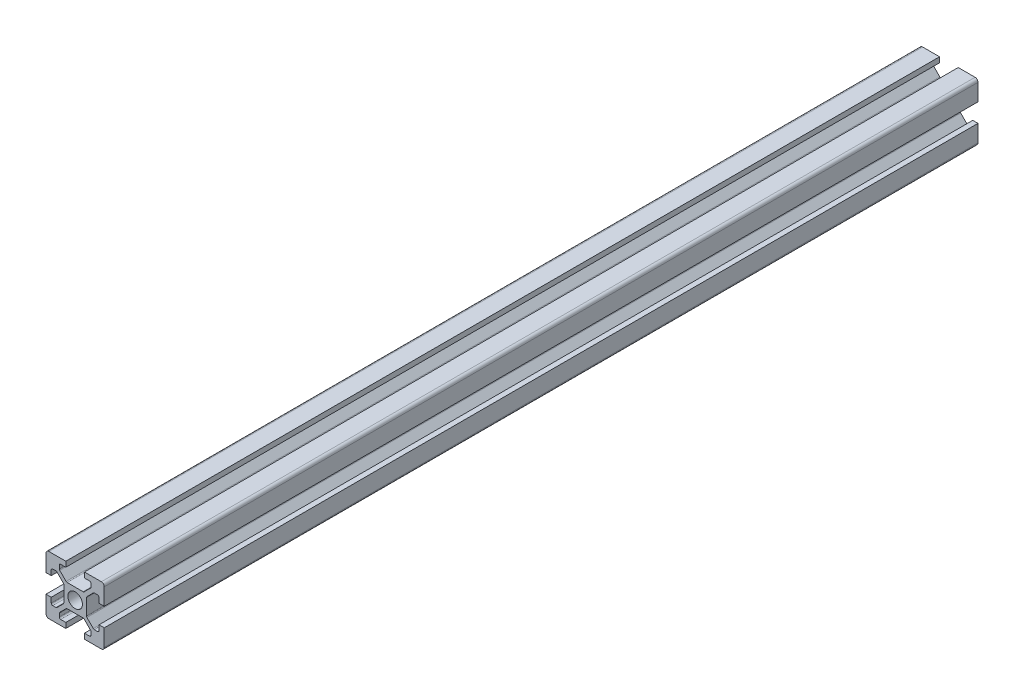
SolidWorks part; units mm, degrees
material "1060 Alloy"
ref_plane "Front Plane" through (0, 0, 0) normal (0, 0, 1) x (1, 0, 0)
ref_plane "Top Plane" through (0, 0, 0) normal (0, 1, 0) x (1, 0, 0)
ref_plane "Right Plane" through (0, 0, 0) normal (1, 0, 0) x (0, 0, -1)
sketch "Sketch1" plane through (0, 0, 0) normal (0, 0, 1) x (1, 0, 0)
  line L0 (20, 0) -> (-8.059, 28.059) construction
  line L1 (0, 0) -> (6.8, 0)
  line L2 (0, 0) -> (0, 6.8)
  line L3 (0, 20) -> (6.8, 20)
  line L4 (20, 0) -> (20, 6.8)
  line L5 (6.8, 20) -> (6.8, 18.2)
  line L6 (20, 20) -> (8.2322, 8.2322) construction
  line L7 (12.95, 6.1) -> (7.05, 6.1)
  line L8 (13.9, 7.05) -> (13.9, 12.95)
  line L9 (12.95, 13.9) -> (7.05, 13.9)
  line L10 (6.1, 7.05) -> (6.1, 12.95)
  line L11 (13.9, 6.1) -> (6.1, 13.9) construction
  line L12 (13.9, 13.9) -> (6.1, 6.1) construction
  line L13 (4.55, 16.4) -> (7.05, 13.9)
  line L14 (13.2, 18.2) -> (13.2, 20)
  line L15 (1.8, 6.8) -> (0, 6.8)
  line L16 (0, 13.2) -> (0, 20)
  line L17 (0, 13.2) -> (1.8, 13.2)
  line L18 (10, 10) -> (10, 13.9) construction
  line L19 (16.4, 4.55) -> (13.9, 7.05)
  line L20 (4.55, 16.4) -> (4.55, 18.2)
  line L21 (4.55, 18.2) -> (6.8, 18.2)
  line L22 (13.2, 18.2) -> (15.45, 18.2)
  line L23 (15.45, 18.2) -> (15.45, 16.4)
  line L24 (15.45, 16.4) -> (12.95, 13.9)
  line L25 (16.4, 4.55) -> (18.2, 4.55)
  line L26 (18.2, 4.55) -> (18.2, 6.8)
  line L27 (20, 6.8) -> (18.2, 6.8)
  line L28 (18.2, 13.2) -> (20, 13.2)
  line L29 (18.2, 13.2) -> (18.2, 15.45)
  line L30 (18.2, 15.45) -> (16.4, 15.45)
  line L31 (16.4, 15.45) -> (13.9, 12.95)
  line L32 (1.8, 4.55) -> (3.6, 4.55)
  line L33 (3.6, 15.45) -> (6.1, 12.95)
  line L34 (3.6, 15.45) -> (1.8, 15.45)
  line L35 (1.8, 15.45) -> (1.8, 13.2)
  line L36 (0, 13.2) -> (1.8, 13.2)
  line L37 (1.8, 6.8) -> (0, 6.8)
  line L38 (3.6, 4.55) -> (6.1, 7.05)
  line L39 (1.8, 6.8) -> (1.8, 4.55)
  line L40 (15.45, 3.6) -> (12.95, 6.1)
  line L41 (4.55, 3.6) -> (7.05, 6.1)
  line L42 (4.55, 1.8) -> (4.55, 3.6)
  line L43 (6.8, 1.8) -> (4.55, 1.8)
  line L44 (6.8, 1.8) -> (6.8, 0)
  line L45 (15.45, 3.6) -> (15.45, 1.8)
  line L46 (15.45, 1.8) -> (13.2, 1.8)
  line L47 (13.2, 0) -> (13.2, 1.8)
  line L48 (13.2, 20) -> (20, 20)
  line L49 (20, 13.2) -> (20, 20)
  line L50 (13.2, 0) -> (20, 0)
  line L51 (6.1, 6.1) -> (-5.5045, -5.5045) construction
  circle A0 centre (10, 10) radius 2.5
  point P25 (10, 16.4)
  point P39 (13.2, 19.1)
  point P46 (0.9, 6.8)
  dimension "D3" = 5
  dimension "D2" = 20
  dimension "D4" = 7.8
  dimension "D5" = 7.8
  dimension "D6" = 6.8
  dimension "D7" = 6.8
  dimension "D8" = 1.8
  dimension "D9" = 10.9
  dimension "D10" = 1.8
  dimension "D11" = 10.9
  dimension "D12" = 20
extrude "Boss-Extrude1" add sketch "Sketch1" along normal mid plane 300 contours L47 L50 L4 L27 L26 L25 L19 L8 L31 L30 L29 L28 L49 L48 L14 L22 L23 L24 L9 L13 L20 L21 L5 L3 L16 L17 L35 L34 L33 L10 L38 L32 L39 L15 L2 L1 L44 L43 L42 L41 L7 L40 L45 L46 A0
fillet "Fillet1" radius 1 4 edges at (20, 20, 0) (20, 0, 0) (0, 0, 0) (0, 20, 0)
fillet "Fillet2" radius 0.5 6 edges at (4.55, 18.2, 0) (4.55, 16.4, 0) (7.05, 13.9, 0) (15.45, 18.2, 0) (15.45, 16.4, 0) (12.95, 13.9, 0)
fillet "Fillet3" radius 0.5 6 edges at (18.2, 15.45, 0) (16.4, 15.45, 0) (13.9, 12.95, 0) (18.2, 4.55, 0) (13.9, 7.05, 0) (16.4, 4.55, 0)
fillet "Fillet4" radius 0.5 6 edges at (1.8, 15.45, 0) (3.6, 15.45, 0) (6.1, 12.95, 0) (3.6, 4.55, 0) (1.8, 4.55, 0) (6.1, 7.05, 0)
fillet "Fillet5" radius 0.5 6 edges at (7.05, 6.1, 0) (4.55, 3.6, 0) (4.55, 1.8, 0) (15.45, 1.8, 0) (15.45, 3.6, 0) (12.95, 6.1, 0)
